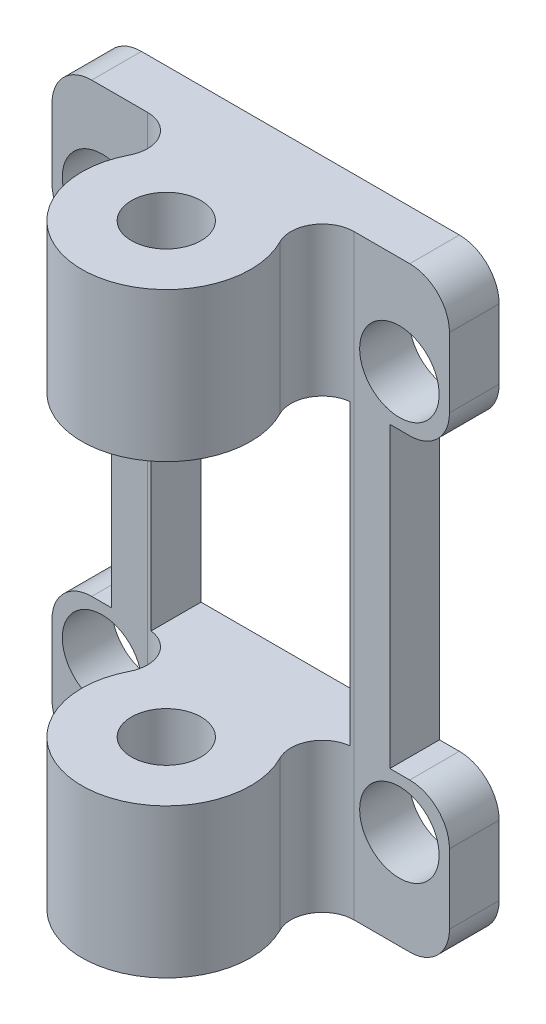
SolidWorks part; units mm, degrees
material "ABS"
ref_plane "Front Plane" through (0, 0, 0) normal (0, 0, 1) x (1, 0, 0)
ref_plane "Top Plane" through (0, 0, 0) normal (0, 1, 0) x (1, 0, 0)
ref_plane "Right Plane" through (0, 0, 0) normal (1, 0, 0) x (0, 0, -1)
sketch "Sketch1" plane through (0, 0, 0) normal (0, 1, 0) x (1, 0, 0)
  line L0 (-963.5599, 0) -> (47214.4337, 0) construction
  line L1 (-963.5599, 2.1415) -> (47214.4337, 2.1415) construction
  line L2 (-12.7, 8.5724) -> (12.7, 8.5724)
  line L3 (0, 5.1566) -> (0, -9.7633) construction
  line L4 (-12.7, 8.5724) -> (-12.7, 5.3974)
  line L5 (12.7, 8.5724) -> (12.7, 5.3974)
  line L6 (-15.9536, 5.3974) -> (11.8773, 5.3974) construction
  line L7 (-12.7, 5.3974) -> (-6.6003, 5.3974)
  line L8 (4.8043, -3.6981) -> (4.8043, 2.46) construction
  line L10 (0.0272, 5.3974) -> (0, 5.3974)
  line L11 (6.6003, 5.3974) -> (12.7, 5.3974)
  circle A0 centre (0, 0) radius 2.2225
  arc A1 (-4.8043, 2.46) -> (4.8043, 2.46) centre (0, 0) ccw
  arc A2 (4.8043, 2.46) -> (6.6003, 5.3974) centre (6.6003, 3.3797) cw
  arc A3 (-4.8043, 2.46) -> (-6.6003, 5.3974) centre (-6.6003, 3.3797) ccw
  arc A4 (-4.8043, 2.46) -> (4.8043, 2.46) centre (0, 0) ccw
  arc A5 (-4.8043, 2.46) -> (4.8043, 2.46) centre (0, 0) ccw
  arc A6 (0.0272, 5.3974) -> (0, 5.3975) centre (0, 0) ccw
  point P21 (-4.8043, 2.46)
  point P24 (4.5813, 2.3136)
  dimension "D1" = 3.175
  dimension "D2" = 4.445
  dimension "D3" = 3.175
  dimension "D7" = 9.3856
  dimension "D9" = 12.7
  dimension "D4" = 2.0178
  dimension "D5" = 25.4
extrude "Boss-Extrude1" add sketch "Sketch1" along normal blind 38.1
sketch "Sketch3" plane through (0, 0, -8.5724) normal (0, 0, -1) x (-1, 0, 0)
  line L0 (0, 40.7645) -> (0, -3.5277) construction
  line L1 (-16.4302, 19.05) -> (13.4107, 19.05) construction
  line L3 (-6.35, 28.575) -> (6.35, 28.575)
  line L4 (-6.35, 28.575) -> (-6.35, 9.525)
  line L5 (-6.35, 9.525) -> (6.35, 9.525)
  line L6 (6.35, 28.575) -> (6.35, 9.525)
  line L7 (-6.35, 28.575) -> (6.35, 9.525) construction
  line L8 (-6.35, 9.525) -> (6.35, 28.575) construction
  point P3 (0, 19.05)
  dimension "D1" = 12.7
  dimension "D2" = 19.05
extrude "Cut-Extrude2" cut sketch "Sketch3" against normal through all
sketch "Sketch8" plane through (0, 0, -5.3974) normal (0, 0, 1) x (1, 0, 0)
  line L0 (-12.7, 38.1) -> (-12.7, 0) construction
  line L1 (-12.7, 28.575) -> (-8.89, 28.575)
  line L2 (-12.7, 28.575) -> (-12.7, 9.525)
  line L3 (-12.7, 9.525) -> (-8.89, 9.525)
  line L4 (-8.89, 28.575) -> (-8.89, 9.525)
  line L5 (12.7, 38.1) -> (12.7, 0) construction
  line L6 (12.7, 28.575) -> (8.89, 28.575)
  line L7 (12.7, 28.575) -> (12.7, 9.525)
  line L8 (12.7, 9.525) -> (8.89, 9.525)
  line L9 (8.89, 28.575) -> (8.89, 9.525)
  dimension "D1" = 3.81
  dimension "D2" = 19.05
extrude "Cut-Extrude4" cut sketch "Sketch8" against normal through all
fillet "Fillet1" radius 2.54 1 edges at (12.7, 38.1, -6.9849)
fillet "Fillet2" radius 2.54 1 edges at (-12.7, 38.1, -6.9849)
fillet "Fillet3" radius 2.54 1 edges at (-12.7, 28.575, -6.9849)
fillet "Fillet4" radius 2.54 1 edges at (12.7, 9.525, -6.9849)
fillet "Fillet5" radius 2.54 1 edges at (12.7, 28.575, -6.9849)
fillet "Fillet6" radius 2.54 1 edges at (-12.7, 9.525, -6.9849)
fillet "Fillet7" radius 2.54 1 edges at (-12.7, 0, -6.9849)
fillet "Fillet8" radius 2.54 1 edges at (12.7, 0, -6.9849)
sketch "Sketch9" plane through (0, 0, -8.5724) normal (0, 0, -1) x (-1, 0, 0)
  line L0 (12.7, 35.56) -> (12.7, 31.115) construction
  line L1 (12.7, 6.985) -> (12.7, 2.54) construction
  line L2 (-12.7, 6.985) -> (-12.7, 2.54) construction
  line L3 (9.5, 31.8) -> (-9.5, 6.3) construction
  line L4 (-9.5, 31.8) -> (9.5, 6.3) construction
  line L5 (6.35, 9.525) -> (6.35, 28.575) construction
  line L6 (6.35, 28.575) -> (-6.35, 28.575) construction
  circle A0 centre (9.5, 31.8) radius 2.54
  circle A1 centre (-9.5, 31.8) radius 2.54
  circle A2 centre (9.5, 6.3) radius 2.54
  circle A3 centre (-9.5, 6.3) radius 2.54
  point P8 (0, 19.05)
  point P11 (6.35, 19.05)
  point P20 (0, 28.575)
  dimension "D1" = 5.08
  dimension "D2" = 19
  dimension "D3" = 25.5
extrude "Cut-Extrude5" cut sketch "Sketch9" against normal through all
